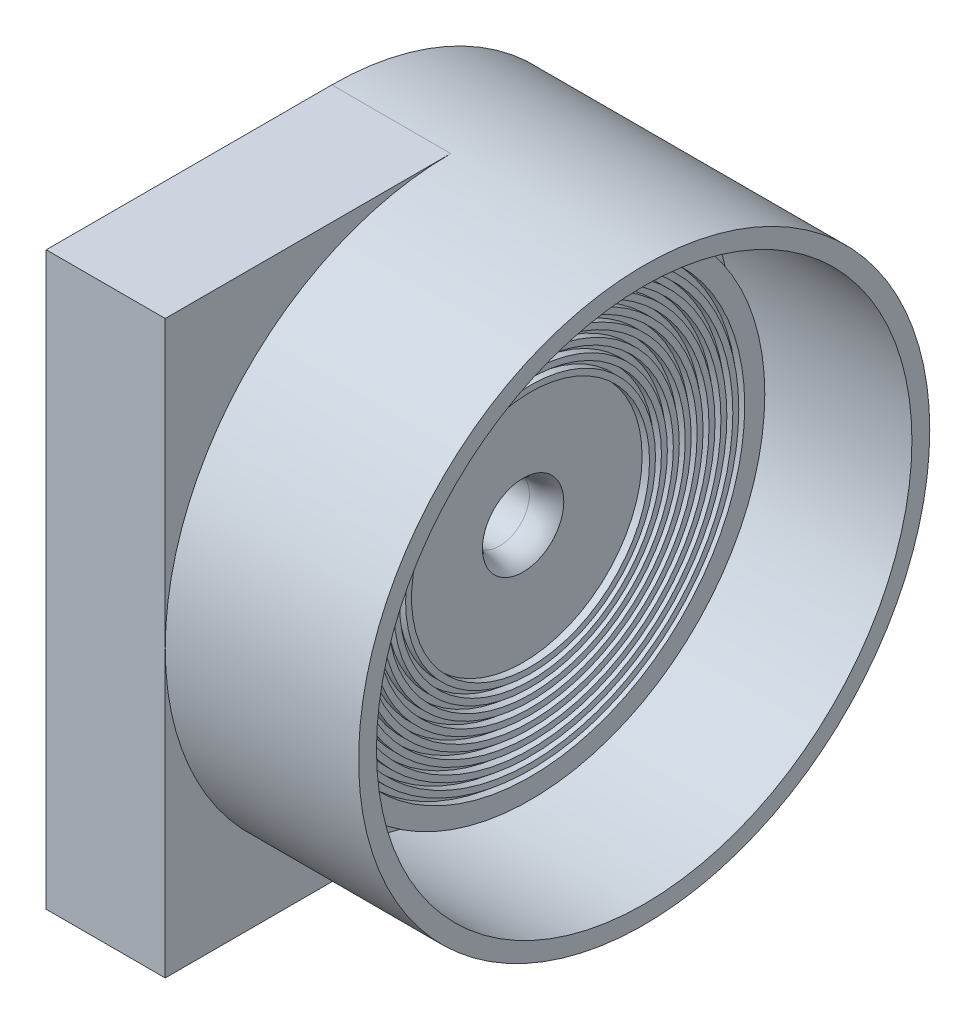
SolidWorks part; units mm, degrees
ref_plane "Front Plane" through (0, 0, 0) normal (0, 0, 1) x (1, 0, 0)
ref_plane "Top Plane" through (0, 0, 0) normal (0, 1, 0) x (1, 0, 0)
ref_plane "Right Plane" through (0, 0, 0) normal (1, 0, 0) x (0, 0, -1)
sketch "Sketch1" plane through (0, 0, 0) normal (1, 0, 0) x (0, 0, -1)
  circle A0 centre (0, 0) radius 43.815
  dimension "D1" = 87.63
extrude "Housing Fitting Extrude" add sketch "Sketch1" along normal blind 17.018
sketch "Sketch2" plane through (0, 0, 0) normal (-1, 0, 0) x (0, 0, 1)
  line L0 (60.96, 0) -> (60.96, 60.96)
  line L1 (60.96, 60.96) -> (0, 60.96)
  line L2 (60.96, 0) -> (60.96, -54.61)
  line L3 (60.96, -60.96) -> (-60.96, -60.96)
  line L7 (0, -55) -> (0, 55) construction
  line L11 (-60.96, 0) -> (-60.96, -54.61)
  line L12 (60.96, -60.96) -> (60.96, -54.61)
  line L13 (-60.96, -60.96) -> (-60.96, -54.61)
  arc A0 (0, 60.96) -> (-60.96, 0) centre (0, 0) ccw
extrude "Housing Body 1" add sketch "Sketch2" along normal blind 25.4 contours A0 L11 L13 L3 L12 L2 L0 L1
sketch "Sketch3" plane through (17.018, 0, 0) normal (1, 0, 0) x (0, 0, -1)
  circle A0 centre (0, 0) radius 6.3754
  dimension "D1" = 12.7508
extrude "Impeller Bore" cut sketch "Sketch3" against normal blind 17.018
ref_plane "O-Ring Sketch Plane" through (8.509, 0, 0) normal (1, 0, 0) x (0, 0, -1)
sketch "Sketch5" plane through (8.509, 0, 0) normal (1, 0, 0) x (0, 0, -1)
  circle A0 centre (0, 0) radius 43.942
  circle A1 centre (0, 0) radius 43.18
extrude "O-Ring Cut" cut sketch "Sketch5" against normal blind 1.27 and the other way blind 1.27
sketch "Sketch8" plane through (-25.4, 0, 0) normal (-1, 0, 0) x (0, 0, 1)
  circle A1 centre (52.959, 0) radius 3.175
extrude "Fastening Bore" [suppressed] cut sketch "Sketch8" against normal blind 19.05
sketch "Sketch10" plane through (0, 0, 60.96) normal (0, 0, 1) x (1, 0, 0)
  line L0 (0, -60.96) -> (0, 60.96) construction
  line L1 (-25.4, 60.96) -> (0, 60.96)
  line L2 (-25.4, 60.96) -> (-25.4, 10.16)
  line L3 (-25.4, 10.16) -> (0, 10.16)
  line L4 (0, 60.96) -> (0, 10.16)
extrude "Discharge Cut" [suppressed] cut sketch "Sketch10" against normal blind 10.541
sketch "Sketch13" plane through (0, 0, 60.96) normal (0, 0, 1) x (1, 0, 0)
  circle A1 centre (-9.525, -41.8177) radius 3.175
extrude "Cut-Extrude3" [suppressed] cut sketch "Sketch13" against normal blind 16.51
sketch "Sketch14" plane through (0, -60.96, 0) normal (0, -1, 0) x (1, 0, 0)
  line L0 (-25.4, 60.96) -> (0, 60.96) construction
  line L1 (-25.4, -60.96) -> (0, -60.96) construction
  circle A0 centre (-9.525, -41.91) radius 3.3734
  circle A1 centre (-9.525, 41.91) radius 3.3734
  dimension "D1" = 6.7469
  dimension "D3" = 6.7469
  dimension "D2" = 19.05
  dimension "D4" = 19.05
extrude "Cut-Extrude4" cut sketch "Sketch14" against normal blind 19.05
sketch "Sketch15" plane through (0, 0, -60.96) normal (0, 0, -1) x (-1, 0, 0)
  line L0 (25.4, -60.96) -> (0, -60.96) construction
  circle A0 centre (9.525, -35.56) radius 3.3734
  dimension "D1" = 6.7469
  dimension "D2" = 25.4
extrude "Cut-Extrude5" cut sketch "Sketch15" against normal blind 19.05
fillet "Fillet1" radius 6.604 1 edges at (17.018, 0, -6.3754)
sketch "Sketch20" plane through (0, 0, 0) normal (1, 0, 0) x (0, 0, -1)
  circle A0 centre (0, 0) radius 60.96
  circle A1 centre (0, 0) radius 43.815
  dimension "D1" = 121.92
  dimension "D2" = 87.63
extrude "Boss-Extrude1" add sketch "Sketch20" along normal blind 3.175
sketch "Sketch21" plane through (3.175, 0, 0) normal (1, 0, 0) x (0, 0, -1)
  circle A0 centre (0, 0) radius 60.96
  circle A1 centre (0, 0) radius 57.15
  dimension "D1" = 121.92
  dimension "D2" = 114.3
extrude "Boss-Extrude2" add sketch "Sketch21" along normal blind 38.1
sketch "Sketch23" plane through (3.175, 0, 0) normal (1, 0, 0) x (0, 0, -1)
  circle A0 centre (0, 0) radius 50.0062
  circle A1 centre (0, 0) radius 43.815
  dimension "D1" = 100.0125
  dimension "D2" = 87.63
extrude "Boss-Extrude3" add sketch "Sketch23" along normal up to surface (13.843 mm away) up to face at (17.018, 0, -12.9794)
sketch "Sketch25" plane through (-25.4, 0, 0) normal (-1, 0, 0) x (0, 0, 1)
  line L0 (0, 0) -> (37.7772, 4.9487) construction
  circle A0 centre (37.7772, 4.9487) radius 3.3734
  circle A1 centre (0, 0) radius 38.1 construction
  circle A2 centre (30.2118, -23.2133) radius 3.3734
  circle A3 centre (4.9487, -37.7772) radius 3.3734
  circle A4 centre (-23.2133, -30.2118) radius 3.3734
  circle A5 centre (-37.7772, -4.9487) radius 3.3734
  circle A6 centre (-30.2118, 23.2133) radius 3.3734
  circle A7 centre (-4.9487, 37.7772) radius 3.3734
  circle A8 centre (23.2133, 30.2118) radius 3.3734
  dimension "D1" = 6.7469
  dimension "D2" = 8
  dimension "D3" = 38.1
extrude "Cut-Extrude13" cut sketch "Sketch25" against normal up to surface (25.4 mm away) up to face at (0, -44.8484, -44.8484)
sketch "Sketch26" plane through (-25.4, 0, 0) normal (-1, 0, 0) x (0, 0, 1)
  circle A0 centre (0, 0) radius 12.954
  dimension "D1" = 25.908
extrude "Cut-Extrude14" cut sketch "Sketch26" against normal offset from surface (25.908 mm away) 16.51 up to face at (17.018, 0, -12.9794)
sketch "Sketch29" plane through (17.018, 0, 0) normal (1, 0, 0) x (0, 0, -1)
  circle A0 centre (0, 0) radius 31.75
  circle A1 centre (0, 0) radius 33.02
  circle A2 centre (0, 0) radius 34.29
  circle A3 centre (0, 0) radius 35.56
  circle A4 centre (0, 0) radius 36.83
  circle A5 centre (0, 0) radius 38.1
  circle A6 centre (0, 0) radius 39.37
  circle A7 centre (0, 0) radius 40.64
  circle A9 centre (0, 0) radius 41.91
  circle A10 centre (0, 0) radius 43.18
  circle A11 centre (0, 0) radius 44.45
  circle A12 centre (0, 0) radius 30.48
  circle A13 centre (0, 0) radius 29.21
  circle A14 centre (0, 0) radius 27.94
  circle A15 centre (0, 0) radius 26.67
  circle A16 centre (0, 0) radius 25.4
  circle A17 centre (0, 0) radius 45.72
  dimension "D1" = 63.5
  dimension "D2" = 66.04
  dimension "D3" = 68.58
  dimension "D4" = 71.12
  dimension "D5" = 73.66
  dimension "D6" = 76.2
  dimension "D7" = 78.74
  dimension "D8" = 81.28
  dimension "D9" = 83.82
  dimension "D10" = 86.36
  dimension "D11" = 88.9
  dimension "D12" = 60.96
  dimension "D13" = 58.42
  dimension "D14" = 55.88
  dimension "D15" = 53.34
  dimension "D16" = 50.8
  dimension "D17" = 91.44
extrude "Cut-Extrude16" cut sketch "Sketch29" against normal blind 1.5875 contours A11 | A10 | A9 | A6 | A7 | A5 | A4 | A3 | A2 | A1 | A0 | A17 | A12 | A13 | A14 | A15 | A16
